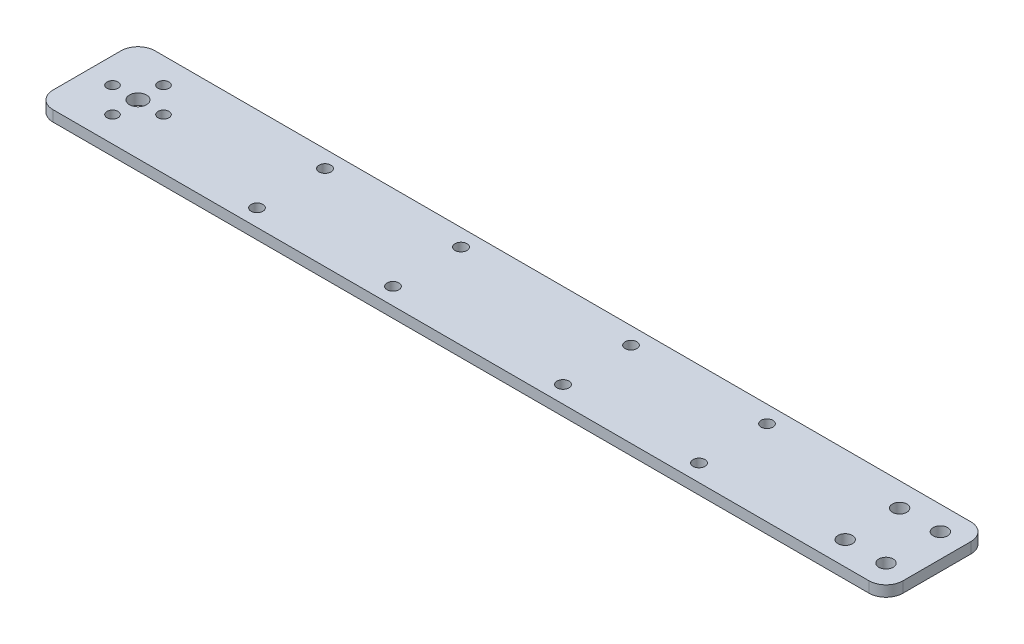
SolidWorks part; units mm, degrees
ref_plane "Front Plane" through (0, 0, 0) normal (0, 0, 1) x (1, 0, 0)
ref_plane "Top Plane" through (0, 0, 0) normal (0, 1, 0) x (1, 0, 0)
ref_plane "Right Plane" through (0, 0, 0) normal (1, 0, 0) x (0, 0, -1)
sketch "Sketch1" plane through (0, 0, 0) normal (0, 1, 0) x (1, 0, 0)
  line L1 (-15, 15) -> (235, 15)
  line L2 (-15, 15) -> (-15, -15)
  line L3 (-15, -15) -> (235, -15)
  line L4 (235, 15) -> (235, -15)
  point P4 (-15, 0)
  dimension "D1" = 250
  dimension "D2" = 30
  dimension "D3" = 15
extrude "Boss-Extrude1" add sketch "Sketch1" along normal blind 3.175
fillet "Fillet1" radius 5 4 edges at (235, 1.5875, 15) (235, 1.5875, -15) (-15, 1.5875, -15) (-15, 1.5875, 15)
sketch "Sketch2" plane through (0, 3.175, 0) normal (0, 1, 0) x (1, 0, 0)
  circle A6 centre (0, 0) radius 2.5
  dimension "D6" = 5
extrude "Cut-Extrude1" cut sketch "Sketch2" against normal through all
sketch "Sketch3" plane through (0, 3.175, 0) normal (0, 1, 0) x (1, 0, 0)
  line L0 (-15, 10) -> (-15, -10) construction
  circle A4 centre (7.5, 0) radius 1.625
  circle A5 centre (0, 0) radius 2.5 construction
  circle A6 centre (0, -7.5) radius 1.625
  circle A7 centre (-7.5, 0) radius 1.625
  circle A8 centre (0, 7.5) radius 1.625
  point P7 (-15, 0)
  dimension "D1" = 7.5
  dimension "D2" = 3.25
  dimension "D3" = 15
extrude "Cut-Extrude3" cut sketch "Sketch3" against normal through all
sketch "Sketch4" plane through (0, 3.175, 0) normal (0, 1, 0) x (1, 0, 0)
  line L0 (-15, 0) -> (235, 0) construction
  line L1 (-15, 10) -> (-15, -10) construction
  line L2 (235, -10) -> (235, 10) construction
  line L3 (110, 15) -> (110, -15) construction
  line L4 (230, 15) -> (-10, 15) construction
  line L5 (-10, -15) -> (230, -15) construction
  line L6 (135, -10) -> (175, -10) construction
  circle A0 centre (85, -10) radius 1.75
  circle A1 centre (135, -10) radius 1.75
  circle A2 centre (135, 10) radius 1.75
  circle A3 centre (85, 10) radius 1.75
  circle A4 centre (175, -10) radius 1.75
  circle A5 centre (175, 10) radius 1.75
  circle A6 centre (45, -10) radius 1.75
  circle A7 centre (45, 10) radius 1.75
  dimension "D3" = 3.5
  dimension "D1" = 25
  dimension "D2" = 5
  dimension "D4" = 40
extrude "Cut-Extrude4" cut sketch "Sketch4" against normal blind 10
sketch "Sketch5" plane through (0, 3.175, 0) normal (0, 1, 0) x (1, 0, 0)
  line L0 (222, 15) -> (222, -15) construction
  line L1 (230, 15) -> (-10, 15) construction
  line L2 (-10, -15) -> (230, -15) construction
  line L3 (235, 0) -> (-15, 0) construction
  line L4 (235, -10) -> (235, 10) construction
  line L5 (-15, 10) -> (-15, -10) construction
  circle A0 centre (216, 8) radius 2.125
  circle A1 centre (228, 8) radius 2.125
  circle A2 centre (228, -8) radius 2.125
  circle A3 centre (216, -8) radius 2.125
  dimension "D2" = 4.25
  dimension "D1" = 6
  dimension "D3" = 8
  dimension "D4" = 13
extrude "Cut-Extrude5" cut sketch "Sketch5" against normal through all
